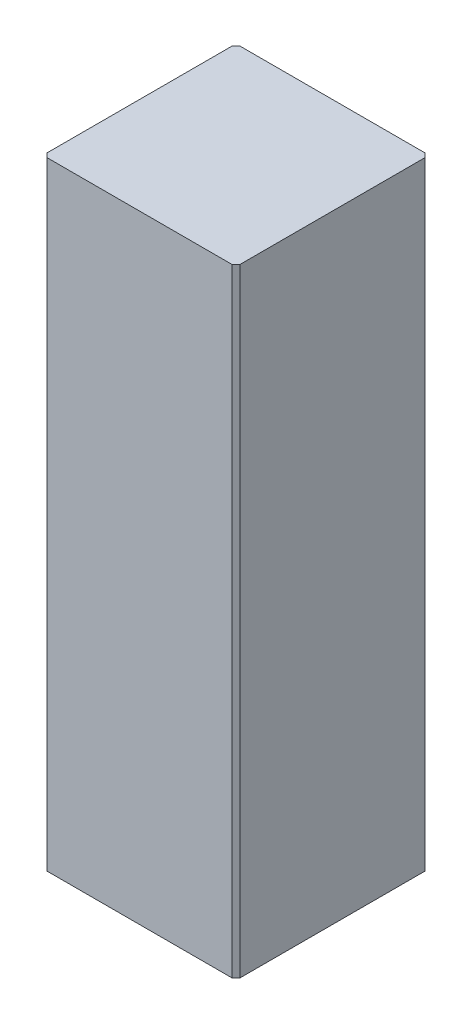
SolidWorks part; units mm, degrees
material "AISI 4130 Steel, normalized at 870C"
ref_plane "X-Y Datum" through (0, 0, 0) normal (0, 0, 1) x (1, 0, 0)
ref_plane "X-Z Datum" through (0, 0, 0) normal (0, 1, 0) x (1, 0, 0)
ref_plane "Y-Z Datum" through (0, 0, 0) normal (1, 0, 0) x (0, 0, -1)
sketch "Sketch1" plane through (0, 0, 0) normal (0, 1, 0) x (1, 0, 0)
  line L1 (0, 0) -> (6.35, 0)
  line L2 (0, 0) -> (0, 6.35)
  line L3 (0, 6.35) -> (6.35, 6.35)
  line L4 (6.35, 0) -> (6.35, 6.35)
  dimension "D1" = 6.35
extrude "Boss-Extrude1" add sketch "Sketch1" along normal blind 20.32
chamfer "Chamfer1" distance 0.127 angle 45 4 edges at (0, 10.16, -6.35) (6.35, 10.16, -6.35) (0, 10.16, 0) (6.35, 10.16, 0)
